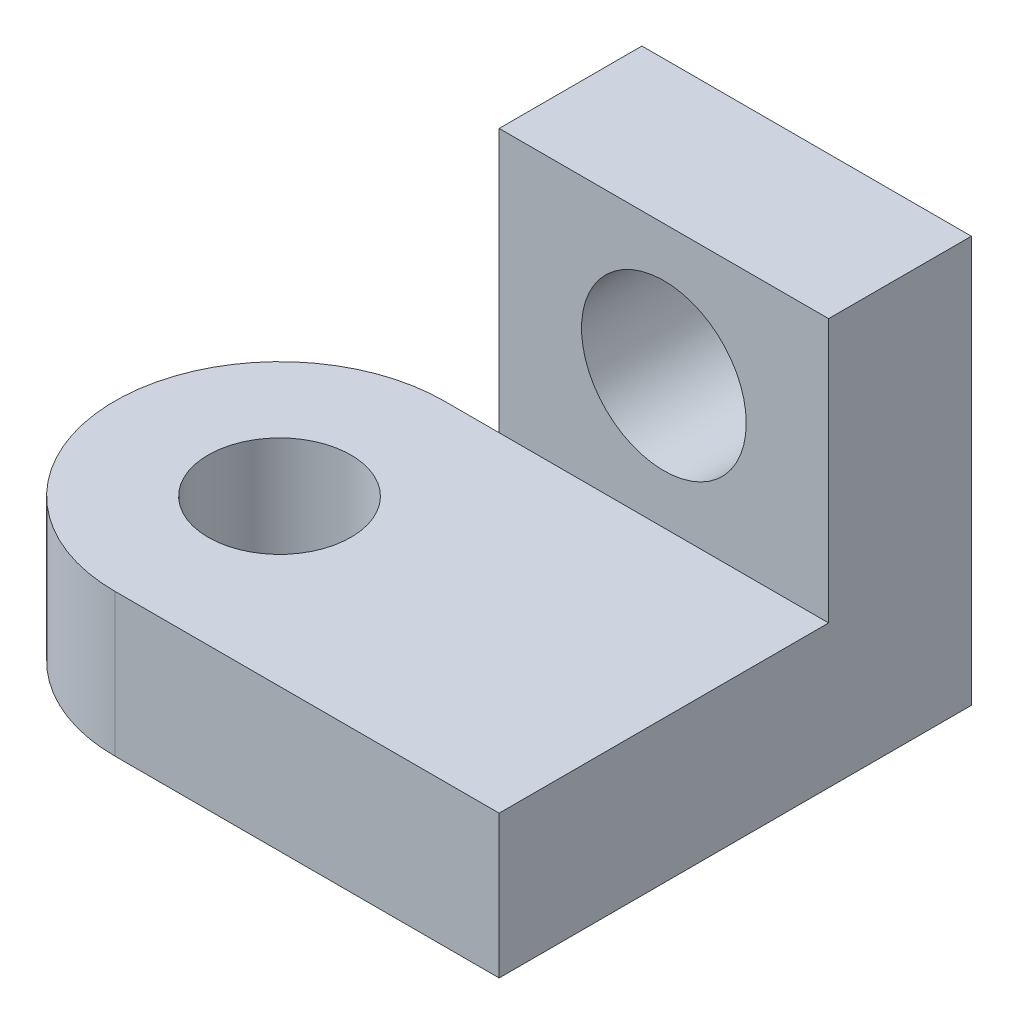
SolidWorks part; units mm, degrees
ref_plane "Front Plane" through (0, 0, 0) normal (0, 0, 1) x (1, 0, 0)
ref_plane "Top Plane" through (0, 0, 0) normal (0, 1, 0) x (1, 0, 0)
ref_plane "Right Plane" through (0, 0, 0) normal (1, 0, 0) x (0, 0, -1)
sketch "Sketch2" plane through (0, 0, 0) normal (1, 0, 0) x (0, 0, -1)
  line L0 (0, 0) -> (0, 37)
  line L1 (0, 37) -> (-13, 37)
  line L2 (-13, 37) -> (-13, 13)
  line L3 (-13, 13) -> (-43, 13)
  line L4 (0, 0) -> (-43, 0)
  line L5 (-43, 13) -> (-43, 0)
  dimension "D1" = 13
  dimension "D2" = 43
  dimension "D3" = 24
  dimension "D4" = 30
extrude "Boss-Extrude3" add sketch "Sketch2" along normal blind 30
sketch "Sketch4" plane through (0, 13, 0) normal (0, 1, 0) x (1, 0, 0)
  line L0 (0, -13) -> (0, -43)
  line L1 (0, -43) -> (-5, -43)
  line L2 (-5, -13) -> (0, -13)
  arc A0 (-5, -43) -> (-5, -13) centre (-5, -28) cw
  circle A3 centre (-5, -28) radius 6.5
  dimension "D2" = 13
  dimension "D1" = 5
extrude "Boss-Extrude5" add sketch "Sketch4" against normal blind 13 contours A0 L2 L0 L1
sketch "Sketch6" plane through (0, 13, 0) normal (0, 1, 0) x (1, 0, 0)
  circle A0 centre (-5, -28) radius 6.5
  dimension "D1" = 13
extrude "Cut-Extrude1" cut sketch "Sketch6" against normal blind 13
sketch "Sketch7" plane through (0, 0, 13) normal (0, 0, 1) x (1, 0, 0)
  line L0 (30, 37) -> (0, 37) construction
  line L2 (0, 37) -> (0, 13) construction
  circle A0 centre (15, 25) radius 7.5
  point P6 (-24.1628, 29.6621)
  point P7 (0, 0)
  dimension "D1" = 15
  dimension "D2" = 12
  dimension "D3" = 15
extrude "Cut-Extrude2" cut sketch "Sketch7" against normal blind 13
